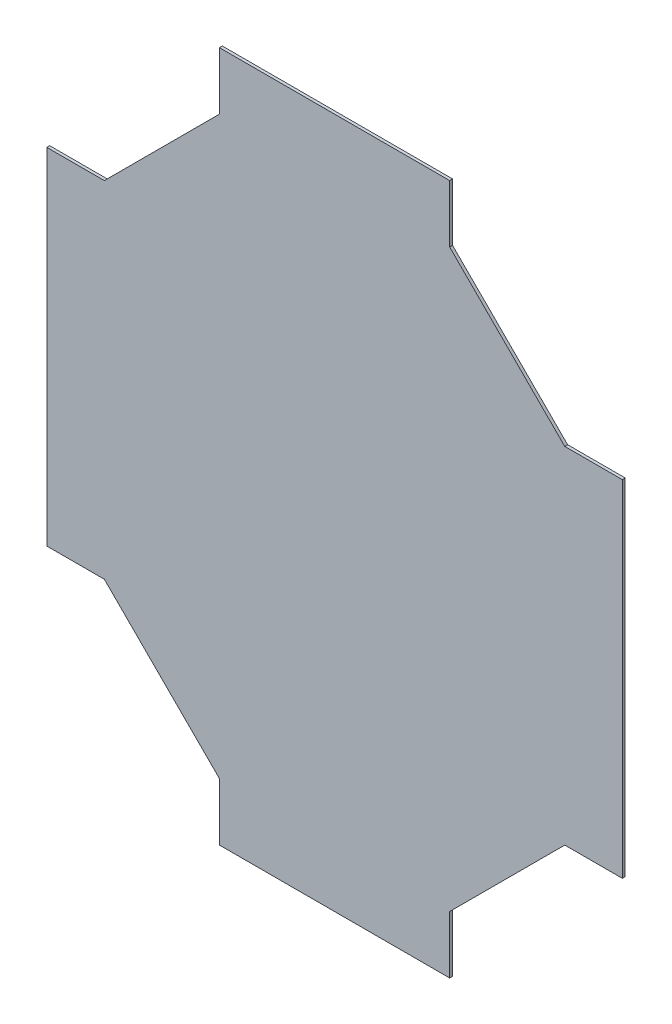
SolidWorks part; units mm, degrees
ref_plane "Front Plane" through (0, 0, 0) normal (0, 0, 1) x (1, 0, 0)
ref_plane "Top Plane" through (0, 0, 0) normal (0, 1, 0) x (1, 0, 0)
ref_plane "Right Plane" through (0, 0, 0) normal (1, 0, 0) x (0, 0, -1)
sketch "Sketch1" plane through (0, 0, 0) normal (0, 0, 1) x (1, 0, 0)
  line L1 (-317.5, 381) -> (317.5, 381)
  line L2 (-317.5, 381) -> (-317.5, -381)
  line L3 (-317.5, -381) -> (317.5, -381)
  line L4 (317.5, 381) -> (317.5, -381)
  line L5 (-317.5, 381) -> (317.5, -381) construction
  line L6 (-317.5, -381) -> (317.5, 381) construction
  point P0 (0, 0)
  dimension "D1" = 762
  dimension "D2" = 635
extrude "Boss-Extrude1" add sketch "Sketch1" along normal blind 3.175
sketch "Sketch3" plane through (0, 0, 3.175) normal (0, 0, 1) x (1, 0, 0)
  line L0 (-127, 381) -> (127, 381)
  line L2 (317.5, 381) -> (-317.5, 381) construction
  line L3 (-317.5, 190.5) -> (-317.5, -190.5)
  line L4 (-467.9177, 497.4577) -> (433.8292, 497.4577)
  line L5 (-317.5, 381) -> (-317.5, -381) construction
  line L6 (317.5, 190.5) -> (317.5, -190.5)
  line L7 (317.5, -381) -> (317.5, 381) construction
  line L8 (-127, -381) -> (127, -381)
  line L9 (-317.5, -381) -> (317.5, -381) construction
  line L10 (-317.5, 190.5) -> (-254, 190.5)
  line L11 (-127, 381) -> (-127, 317.5)
  line L12 (-317.5, -190.5) -> (-254, -190.5)
  line L13 (-127, -381) -> (-127, -317.5)
  line L14 (127, 381) -> (127, 317.5)
  line L15 (317.5, 190.5) -> (254, 190.5)
  line L16 (317.5, -190.5) -> (254, -190.5)
  line L17 (127, -381) -> (127, -317.5)
  line L18 (127, -317.5) -> (254, -190.5)
  line L19 (-254, -190.5) -> (-127, -317.5)
  line L20 (-254, 190.5) -> (-127, 317.5)
  line L21 (127, 317.5) -> (254, 190.5)
  line L22 (-467.9177, 497.4577) -> (-467.9177, -575.7481)
  line L23 (-467.9177, -575.7481) -> (433.8292, -575.7481)
  line L24 (433.8292, 497.4577) -> (433.8292, -575.7481)
  point P5 (0, 381)
  point P10 (-317.5, 0)
  point P15 (317.5, 0)
  point P20 (0, -381)
  dimension "D1" = 63.5
  dimension "D2" = 63.5
  dimension "D3" = 63.5
  dimension "D4" = 63.5
  dimension "D5" = 63.5
  dimension "D6" = 63.5
  dimension "D7" = 63.5
  dimension "D8" = 63.5
  dimension "D9" = 381
extrude "Cut-Extrude1" cut sketch "Sketch3" against normal through all
